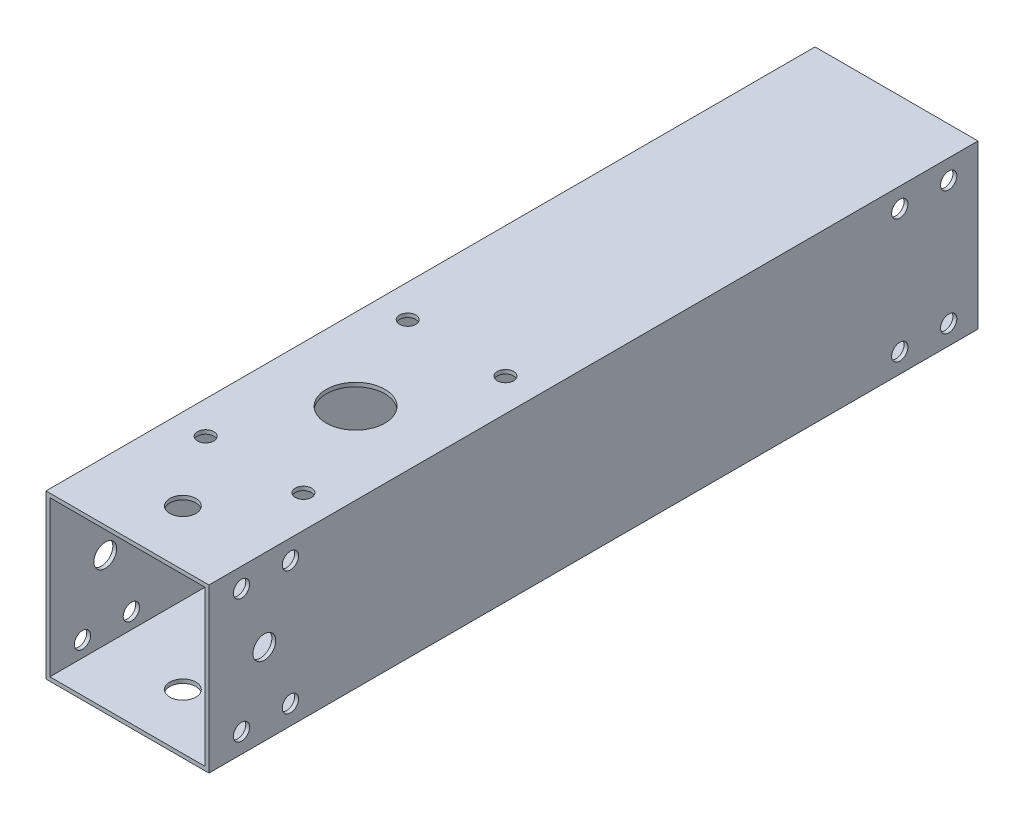
SolidWorks part; units mm, degrees
ref_plane "Alzado" through (0, 0, 0) normal (0, 0, 1) x (1, 0, 0)
ref_plane "Planta" through (0, 0, 0) normal (0, 1, 0) x (1, 0, 0)
ref_plane "Vista lateral" through (0, 0, 0) normal (1, 0, 0) x (0, 0, -1)
sketch "Croquis1" plane through (0, 0, 0) normal (0, 0, 1) x (1, 0, 0)
  line L0 (-23.8, 23.8) -> (-23.8, -23.8)
  line L1 (-25, 25) -> (25, 25)
  line L2 (-25, 25) -> (-25, -25)
  line L3 (-25, -25) -> (25, -25)
  line L4 (25, 25) -> (25, -25)
  line L5 (-25, 25) -> (25, -25) construction
  line L6 (-25, -25) -> (25, 25) construction
  line L7 (-23.8, -23.8) -> (23.8, -23.8)
  line L8 (23.8, 23.8) -> (23.8, -23.8)
  line L9 (-23.8, 23.8) -> (23.8, 23.8)
  point P0 (0, 0)
  dimension "D1" = 50
  dimension "D2" = 50
  dimension "D3" = 1.2
extrude "Saliente-Extruir1" add sketch "Croquis1" along normal blind 237
sketch "Croquis2" plane through (25, 0, 0) normal (1, 0, 0) x (0, 0, -1)
  line L0 (-10, 25) -> (-10, -25) construction
  line L1 (-237, 25) -> (0, 25) construction
  line L2 (-237, -25) -> (0, -25) construction
  line L3 (-25, 25) -> (-25, -25) construction
  line L4 (0, -25) -> (0, 25) construction
  line L5 (0, 19) -> (-25, 19) construction
  line L6 (0, -19) -> (-25, -19) construction
  line L7 (-25, 19) -> (-237, 19) construction
  line L8 (-237, -25) -> (-237, 25) construction
  line L9 (-25, -19) -> (-237, -19) construction
  line L10 (-227, 25) -> (-227, -25) construction
  line L11 (-212, 25) -> (-212, -25) construction
  line L12 (-237, 0) -> (-220, 0) construction
  circle A0 centre (-10, 19) radius 2.5
  circle A1 centre (-25, 19) radius 2.5
  circle A2 centre (-25, -19) radius 2.5
  circle A3 centre (-10, -19) radius 2.5
  circle A4 centre (-227, 19) radius 2.5
  circle A5 centre (-212, 19) radius 2.5
  circle A6 centre (-212, -19) radius 2.5
  circle A7 centre (-227, -19) radius 2.5
  circle A8 centre (-220, 0) radius 3.5
  dimension "D5" = 5
  dimension "D6" = 5
  dimension "D7" = 5
  dimension "D8" = 5
  dimension "D11" = 5
  dimension "D12" = 5
  dimension "D13" = 5
  dimension "D14" = 5
  dimension "D16" = 7
  dimension "D1" = 10
  dimension "D2" = 15
  dimension "D3" = 19
  dimension "D4" = 19
  dimension "D9" = 10
  dimension "D10" = 15
  dimension "D15" = 17
extrude "Cortar-Extruir1" cut sketch "Croquis2" against normal through all
chamfer "Chaflán1" distance 1 angle 45 4 edges at (-25, 0, 0) (0, 25, 0) (25, 0, 0) (0, -25, 0)
sketch "Croquis3" plane through (0, 25, 0) normal (0, 1, 0) x (1, 0, 0)
  line L0 (0, -1) -> (0, -237) construction
  line L1 (25, -1) -> (-25, -1) construction
  line L2 (25, -237) -> (-25, -237) construction
  circle A0 centre (0, -220) radius 4
  dimension "D1" = 8
  dimension "D2" = 17
extrude "Cortar-Extruir2" cut sketch "Croquis3" against normal through all
sketch "Croquis4" plane through (0, 25, 0) normal (0, 1, 0) x (1, 0, 0)
  line L0 (0, -1) -> (0, -237) construction
  line L1 (25, -1) -> (-25, -1) construction
  line L2 (25, -237) -> (-25, -237) construction
  circle A0 centre (0, -167) radius 9
  dimension "D1" = 18
  dimension "D2" = 70
extrude "Cortar-Extruir3" cut sketch "Croquis4" against normal through all
sketch "Croquis5" plane through (0, 25, 0) normal (0, 1, 0) x (1, 0, 0)
  line L1 (-15, -136) -> (15, -136) construction
  line L2 (-15, -136) -> (-15, -198) construction
  line L3 (-15, -198) -> (15, -198) construction
  line L4 (15, -136) -> (15, -198) construction
  line L5 (-15, -136) -> (15, -198) construction
  line L6 (-15, -198) -> (15, -136) construction
  circle A0 centre (-15, -136) radius 2.5
  circle A1 centre (15, -136) radius 2.5
  circle A2 centre (-15, -198) radius 2.5
  circle A3 centre (15, -198) radius 2.5
  point P0 (0, -167)
  dimension "D3" = 5
  dimension "D4" = 5
  dimension "D5" = 5
  dimension "D6" = 5
  dimension "D1" = 62
  dimension "D2" = 30
extrude "Cortar-Extruir4" cut sketch "Croquis5" against normal blind 2
